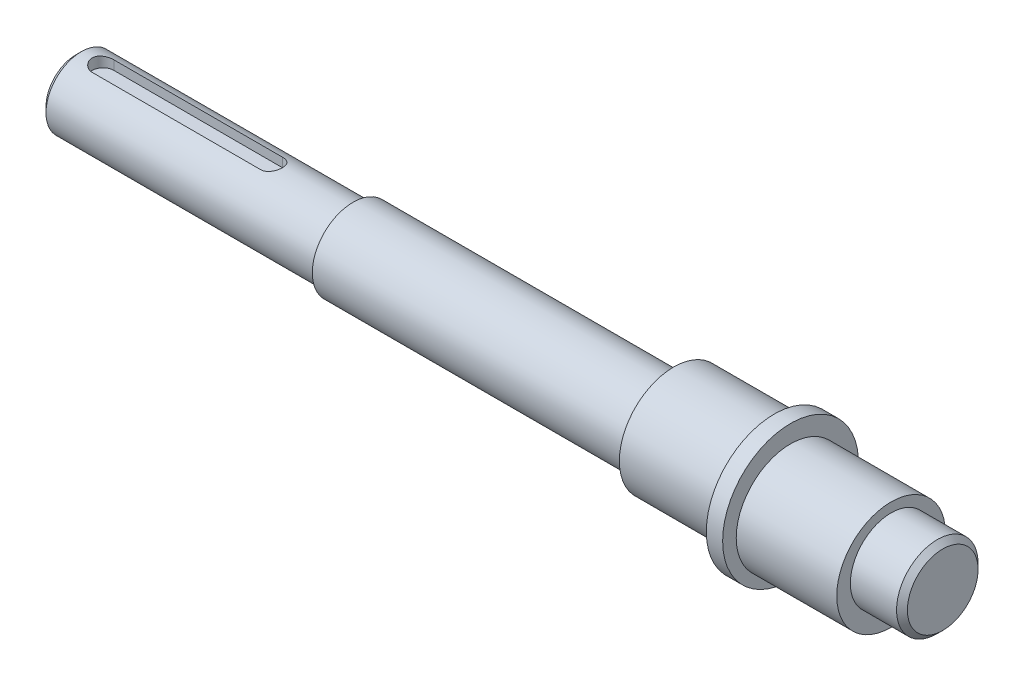
SolidWorks part; units mm, degrees
ref_plane "前视基准面" through (0, 0, 0) normal (0, 0, 1) x (1, 0, 0)
ref_plane "上视基准面" through (0, 0, 0) normal (0, 1, 0) x (1, 0, 0)
ref_plane "右视基准面" through (0, 0, 0) normal (1, 0, 0) x (0, 0, -1)
sketch "草图1" plane through (0, 0, 0) normal (0, 0, 1) x (1, 0, 0)
  line L0 (0, 0) -> (319, 0) construction
  line L1 (55, 0) -> (-55, 0) construction
  line L2 (0, 0) -> (0, 13)
  line L3 (0, -55) -> (0, 55) construction
  line L4 (0, 13) -> (102, 13)
  line L5 (102, 13) -> (102, 15)
  line L6 (102, 15) -> (220, 15)
  line L7 (220, 15) -> (257, 15)
  line L8 (257, 15) -> (257, 25)
  line L9 (257, 25) -> (263, 25)
  line L10 (263, 25) -> (263, 15)
  line L11 (263, 15) -> (300, 15)
  line L12 (0, 0) -> (319, 0)
  line L13 (300, 15) -> (319, 15)
  line L14 (319, 15) -> (319, 0)
  dimension "D1" = 102
  dimension "D2" = 118
  dimension "D3" = 37
  dimension "D4" = 37
  dimension "D5" = 19
  dimension "D6" = 26
  dimension "D7" = 30
  dimension "D8" = 50
  dimension "D9" = 30
  dimension "D10" = 319
revolve "旋转1" add sketch "草图1" angle 360 about L0
sketch "草图2" plane through (0, 0, 0) normal (0, 1, 0) x (1, 0, 0)
  line L0 (10, 0) -> (72, 0) construction
  line L1 (0, 0) -> (319, 0) construction
  line L2 (10, 4) -> (72, 4)
  line L3 (10, -4) -> (72, -4)
  arc A0 (10, 4) -> (10, -4) centre (10, 0) ccw
  arc A1 (72, -4) -> (72, 4) centre (72, 0) ccw
  point P4 (41, 0)
  dimension "D1" = 70
  dimension "D2" = 6
  dimension "D3" = 8
extrude "切除-拉伸1" cut sketch "草图2" against normal blind 4 from vertex at 13 starting at point (0, 13, 0)
sketch "草图3" plane through (257, 0, 0) normal (-1, 0, 0) x (0, 0, 1)
  line L0 (0, 15) -> (0, 0) construction
  circle A0 centre (0, 1.5) radius 20
  dimension "D1" = 40
  dimension "D2" = 1.5
extrude "凸台-拉伸1" add sketch "草图3" along normal blind 37
sketch "草图4" plane through (263, 0, 0) normal (1, 0, 0) x (0, 0, -1)
  line L0 (0, 27.5) -> (0, -27.5) construction
  circle A0 centre (0, -1.5) radius 20
  dimension "D1" = 40
  dimension "D2" = 1.5
extrude "凸台-拉伸2" add sketch "草图4" along normal blind 37
chamfer "倒角1" distance 2 angle 45 2 edges at (0, 0, 13) (319, 0, 15)
sketch "草图5" plane through (0, 0, 0) normal (0, 0, 1) x (1, 0, 0)
  line L0 (69.25, -17.9707) -> (69.25, -3.6351) construction
  line L1 (65.25, -13) -> (69.25, -9)
  line L2 (65.25, -13) -> (69.25, -13)
  line L3 (2, -13) -> (102, -13) construction
  line L4 (0, -27.5) -> (0, 27.5) construction
  line L5 (69.25, -9) -> (69.25, -13)
  point P4 (45.2361, -13)
  dimension "D1" = 45
  dimension "D2" = 8
  dimension "D3" = 69.25
revolve "切除-旋转1" cut sketch "草图5" angle 360 about L0
